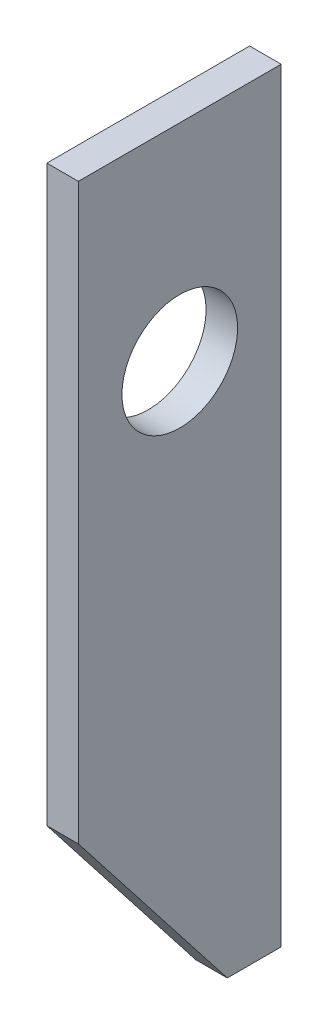
SolidWorks part; units mm, degrees
ref_plane "Спереди" through (0, 0, 0) normal (0, 0, 1) x (1, 0, 0)
ref_plane "Сверху" through (0, 0, 0) normal (0, 1, 0) x (1, 0, 0)
ref_plane "Справа" through (0, 0, 0) normal (1, 0, 0) x (0, 0, -1)
sketch "Эскиз1" plane through (0, 0, 0) normal (1, 0, 0) x (0, 0, -1)
  line L0 (9.643, 36.3483) -> (-9.643, 36.3483)
  line L1 (-9.643, 36.3483) -> (-9.643, -18.2202)
  line L2 (-9.643, -18.2202) -> (4.5203, -36.3483)
  line L3 (4.5203, -36.3483) -> (9.643, -36.3483)
  line L4 (9.643, -36.3483) -> (9.643, 36.3483)
extrude "Бобышка-Вытянуть1" add sketch "Эскиз1" along normal blind 3
sketch "Эскиз2" plane through (0, 0, 0) normal (-1, 0, 0) x (0, 0, 1)
  line L0 (9.643, 9.0641) -> (-9.643, 9.0641) construction
  line L1 (9.643, 36.3483) -> (9.643, -18.2202) construction
  line L2 (-9.643, -36.3483) -> (-9.643, 36.3483) construction
  line L3 (0, 9.0641) -> (0, 36.3483) construction
  line L4 (-9.643, 36.3483) -> (9.643, 36.3483) construction
  circle A0 centre (0, 22.7062) radius 5.5 construction
  circle A1 centre (0, 16.7062) radius 5.5
  dimension "D1" = 2
extrude "Вырез-Вытянуть1" cut sketch "Эскиз2" against normal through all
